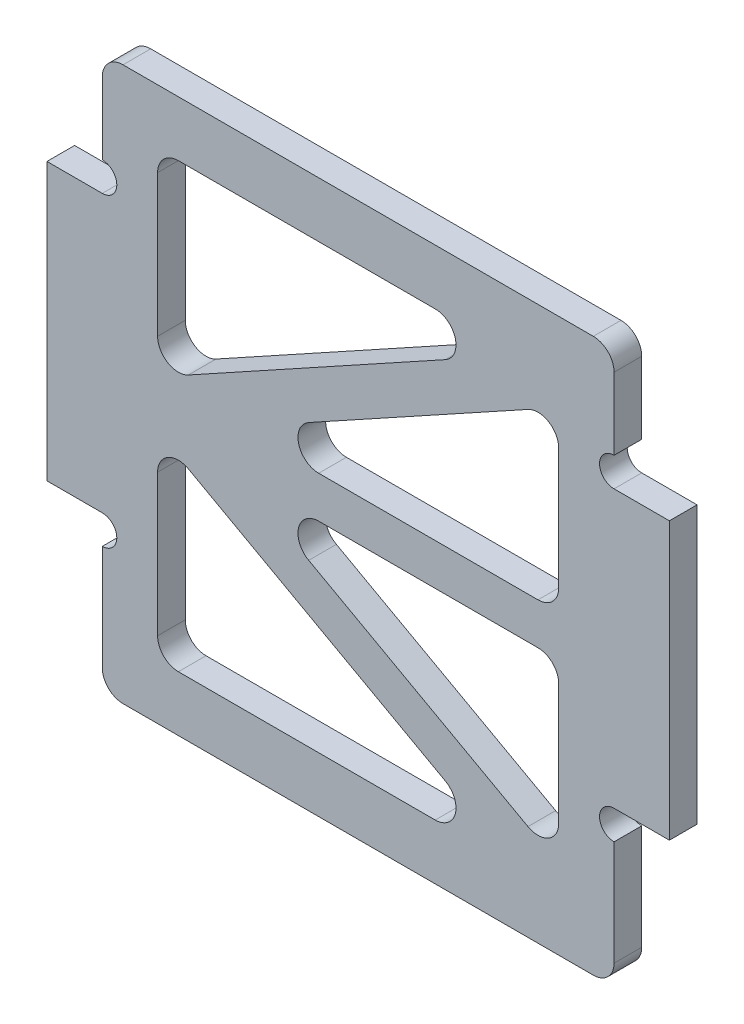
SolidWorks part; units mm, degrees
material "Thornel Mat VMA"
ref_plane "前视基准面" through (0, 0, 0) normal (0, 0, 1) x (1, 0, 0)
ref_plane "上视基准面" through (0, 0, 0) normal (0, 1, 0) x (1, 0, 0)
ref_plane "右视基准面" through (0, 0, 0) normal (1, 0, 0) x (0, 0, -1)
sketch "草图1" plane through (0, 0, 0) normal (0, 0, 1) x (1, 0, 0)
  line L1 (-18.5, -20) -> (18.5, -20)
  line L2 (-18.5, -20) -> (-18.5, 20)
  line L3 (-18.5, 20) -> (18.5, 20)
  line L4 (18.5, -20) -> (18.5, 20)
  line L5 (-18.5, -20) -> (18.5, 20) construction
  line L6 (-18.5, 20) -> (18.5, -20) construction
  point P0 (0, 0)
  dimension "D1" = 40
  dimension "D2" = 37
extrude "凸台-拉伸1" add sketch "草图1" along normal blind 2
sketch "草图2" plane through (18.5, 0, 0) normal (1, 0, 0) x (0, 0, -1)
  line L0 (0, 11.2) -> (-2, 11.2) construction
  line L1 (-2, -8.8) -> (0, -8.8) construction
  line L2 (0, 11.2) -> (-2, 11.2)
  line L3 (-2, -8.8) -> (0, -8.8)
  line L4 (0, 11.2) -> (0, -8.8)
  line L5 (-2, 11.2) -> (-2, -8.8)
extrude "凸台-拉伸2" add sketch "草图2" along normal blind 4
mirror "镜向1" about plane through (0, 0, 0) normal (1, 0, 0) of "凸台-拉伸2"
sketch "草图3" plane through (0, 0, 0) normal (0, 0, -1) x (-1, 0, 0)
  line L0 (18.5, 20) -> (18.5, 11.2) construction
  line L1 (18.5, -8.8) -> (18.5, -20) construction
  line L2 (0, 0) -> (0, 20) construction
  line L3 (-18.5, 20) -> (18.5, 20) construction
  circle A0 centre (18.5, 12.25) radius 1.05
  circle A1 centre (18.5, -9.85) radius 1.05
  circle A2 centre (-18.5, -9.85) radius 1.05
  circle A3 centre (-18.5, 12.25) radius 1.05
  dimension "D1" = 2.1
extrude "切除-拉伸1" cut sketch "草图3" against normal blind 3
sketch "草图4" plane through (0, 0, 0) normal (0, 0, -1) x (-1, 0, 0)
  line L0 (18.5, 20) -> (18.5, 13.3) construction
  line L1 (-14.5, -16) -> (14.5, -16)
  line L2 (-14.5, -16) -> (-14.5, 16)
  line L3 (-14.5, 16) -> (14.5, 16)
  line L4 (14.5, -16) -> (14.5, 16)
  line L5 (0, 16) -> (0, -16) construction
  line L6 (-14.5, 0) -> (14.5, 0) construction
  line L7 (-18.5, 20) -> (18.5, 20) construction
  line L8 (-14.5, 16) -> (14.5, 0) construction
  line L9 (14.5, 0) -> (-14.5, -16) construction
  line L10 (13.7754, 1.3134) -> (-15.2246, -14.6866)
  line L11 (-14.5, -1.5) -> (14.5, -1.5)
  line L12 (-15.2246, 14.6866) -> (13.7754, -1.3134)
  line L13 (15.2246, -1.3134) -> (-13.7754, -17.3134)
  line L14 (-14.5, 1.5) -> (14.5, 1.5)
  line L15 (-13.7754, 17.3134) -> (15.2246, 1.3134)
  arc A0 (13.7754, 1.3134) -> (15.2246, -1.3134) centre (14.5, 0) cw
  arc A1 (-15.2246, -14.6866) -> (-13.7754, -17.3134) centre (-14.5, -16) ccw
  arc A2 (-14.5, -1.5) -> (-14.5, 1.5) centre (-14.5, 0) cw
  arc A3 (14.5, -1.5) -> (14.5, 1.5) centre (14.5, 0) ccw
  arc A4 (-15.2246, 14.6866) -> (-13.7754, 17.3134) centre (-14.5, 16) cw
  arc A5 (13.7754, -1.3134) -> (15.2246, 1.3134) centre (14.5, 0) ccw
  point P0 (0, 0)
  dimension "D1" = 4
  dimension "D2" = 4
  dimension "D3" = 3
  dimension "D4" = 1.5
extrude "切除-拉伸2" cut sketch "草图4" against normal blind 10 contours L4 L13 L1 | L11 L2 L10 | L2 L14 L12 | L3 L15 L4
fillet "圆角1" radius 1.5 16 edges at (-18.5, 20, 1) (-18.5, -20, 1) (18.5, -20, 1) (18.5, 20, 1) (-8.6762, -1.5, 1) (14.5, -14.2868, 1) (14.5, -1.5, 1) (-14.5, 16, 1) (-14.5, 1.7132, 1) (11.3949, 16, 1) (11.3949, -16, 1) (-14.5, -1.7132, 1) (-14.5, -16, 1) (-8.6762, 1.5, 1) (14.5, 1.5, 1) (14.5, 14.2868, 1)
